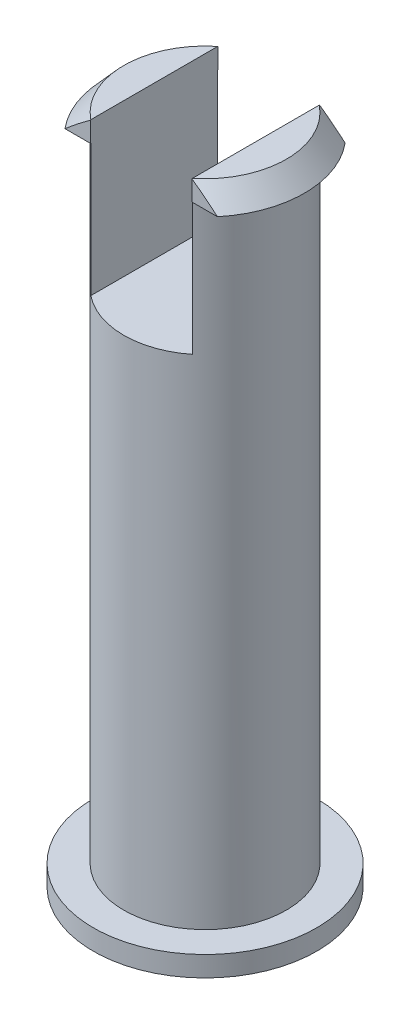
SolidWorks part; units mm, degrees
ref_plane "Front Plane" through (0, 0, 0) normal (0, 0, 1) x (1, 0, 0)
ref_plane "Top Plane" through (0, 0, 0) normal (0, 1, 0) x (1, 0, 0)
ref_plane "Right Plane" through (0, 0, 0) normal (1, 0, 0) x (0, 0, -1)
sketch "Sketch1" plane through (0, 0, 0) normal (0, 1, 0) x (1, 0, 0)
  circle A0 centre (0, 0) radius 4
  dimension "D1" = 8
extrude "Boss-Extrude1" add sketch "Sketch1" along normal blind 32 contours A0
sketch "Sketch4" plane through (0, 0, 0) normal (0, -1, 0) x (1, 0, 0)
  circle A0 centre (0, 0) radius 5.5
  dimension "D1" = 11
extrude "Boss-Extrude3" add sketch "Sketch4" along normal blind 1
ref_plane "Plane1" through (0, 31, 0) normal (0, 1, 0) x (1, 0, 0)
sketch "Sketch5" plane through (0, 31, 0) normal (0, 1, 0) x (1, 0, 0)
  line L1 (-3.75, -3.1421) -> (3.75, -3.1421)
  line L3 (-3.75, 3.1421) -> (3.75, 3.1421)
  arc A0 (-3.75, 3.1421) -> (-3.75, -3.1421) centre (0, 0) ccw
  arc A1 (3.75, -3.1421) -> (3.75, 3.1421) centre (0, 0) ccw
  dimension "D1" = 6.2841
  dimension "D4" = 7.5
  dimension "D5" = 7.5
extrude "Boss-Extrude4" add sketch "Sketch5" along normal blind 1
sketch "Sketch6" plane through (0, 32, 0) normal (0, 1, 0) x (1, 0, 0)
  line L1 (-2.5, -4) -> (2.5, -4)
  line L2 (-2.5, -4) -> (-2.5, 4)
  line L3 (-2.5, 4) -> (2.5, 4)
  line L4 (2.5, -4) -> (2.5, 4)
  line L5 (-2.5, -4) -> (2.5, 4) construction
  line L6 (-2.5, 4) -> (2.5, -4) construction
  point P0 (0, 0)
  dimension "D1" = 5
  dimension "D2" = 8
extrude "Cut-Extrude2" cut sketch "Sketch6" against normal blind 7.5
sketch "Sketch8" plane through (0, 0, 0) normal (0, 0, 1) x (1, 0, 0)
  line L0 (0, 0) -> (0, 32) construction
  line L1 (5.5, 0) -> (-5.5, 0) construction
  line L2 (4.8923, 31) -> (4, 32)
  line L3 (2.5, 32) -> (3.75, 32) construction
  line L4 (4, 32) -> (4.8923, 32)
  line L5 (4.8923, 32) -> (4.8923, 31)
  dimension "D1" = 32
  dimension "D2" = 4
revolve "Cut-Revolve1" cut sketch "Sketch8" angle 360 about L0
